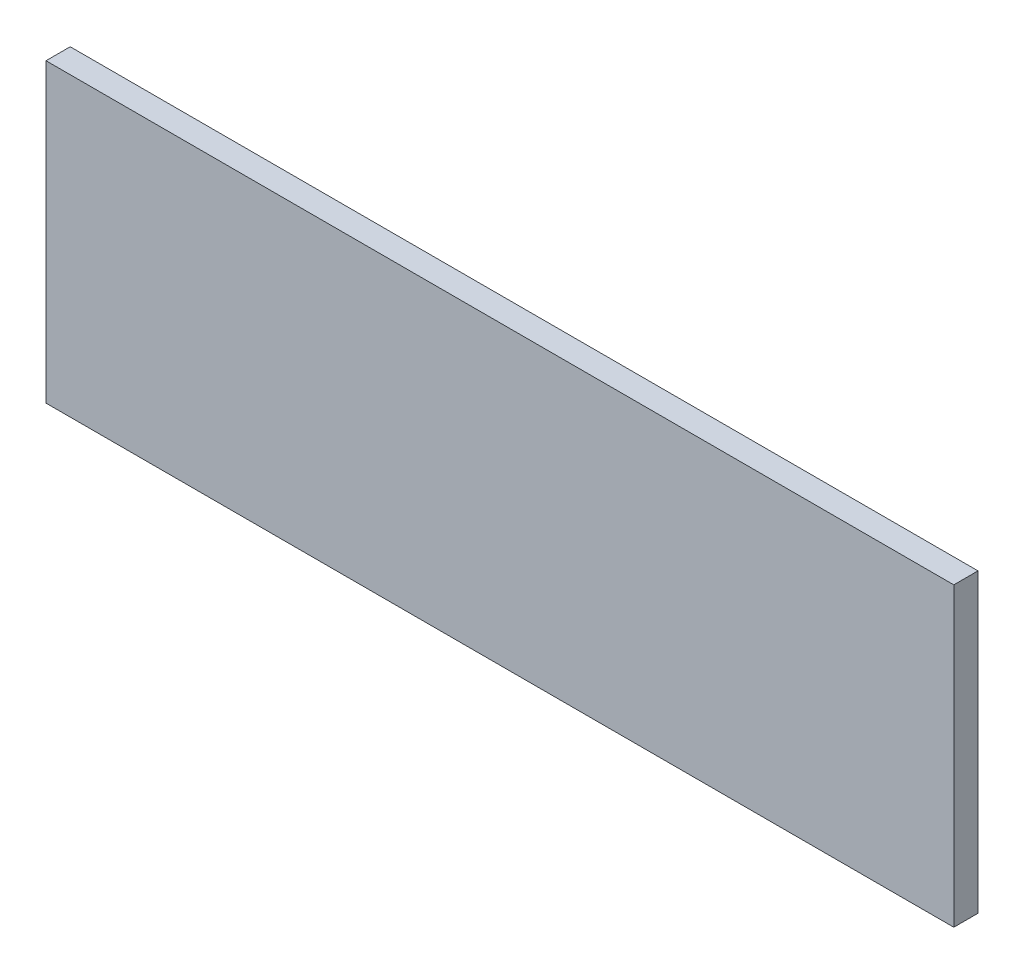
SolidWorks part; units mm, degrees
ref_plane "Alzado" through (0, 0, 0) normal (0, 0, 1) x (1, 0, 0)
ref_plane "Planta" through (0, 0, 0) normal (0, 1, 0) x (1, 0, 0)
ref_plane "Vista lateral" through (0, 0, 0) normal (1, 0, 0) x (0, 0, -1)
sketch "Croquis1" plane through (0, 0, 0) normal (0, 0, 1) x (1, 0, 0)
  line L1 (37.5, 12.25) -> (-37.5, 12.25)
  line L2 (37.5, 12.25) -> (37.5, -12.25)
  line L3 (37.5, -12.25) -> (-37.5, -12.25)
  line L4 (-37.5, 12.25) -> (-37.5, -12.25)
  line L5 (37.5, 12.25) -> (-37.5, -12.25) construction
  line L6 (37.5, -12.25) -> (-37.5, 12.25) construction
  point P0 (0, 0)
extrude "Saliente-Extruir1" add sketch "Croquis1" along normal blind 2
